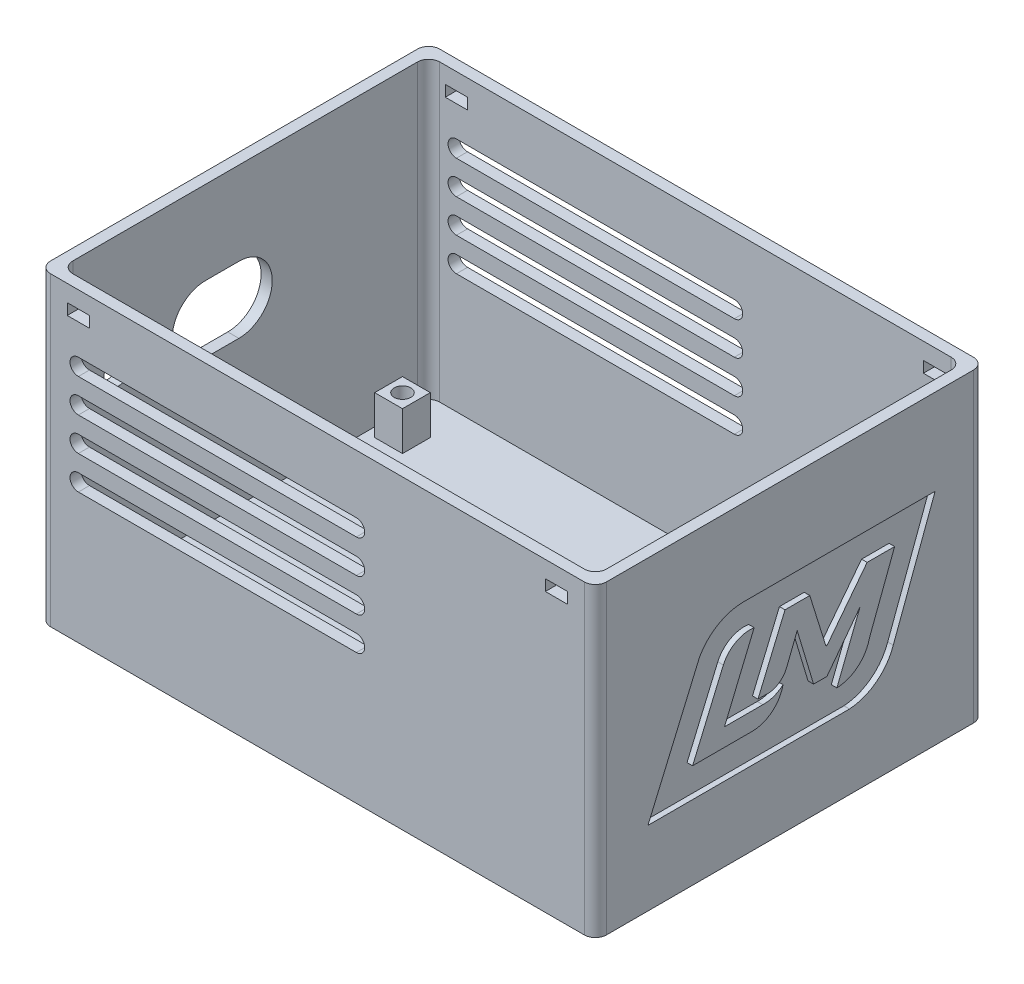
SolidWorks part; units mm, degrees
ref_plane "Front Plane" through (0, 0, 0) normal (0, 0, 1) x (1, 0, 0)
ref_plane "Top Plane" through (0, 0, 0) normal (0, 1, 0) x (1, 0, 0)
ref_plane "Right Plane" through (0, 0, 0) normal (1, 0, 0) x (0, 0, -1)
sketch "Sketch1" plane through (0, 0, 0) normal (0, 1, 0) x (1, 0, 0)
  line L1 (-50, 35) -> (50, 35)
  line L2 (-50, 35) -> (-50, -35)
  line L3 (-50, -35) -> (50, -35)
  line L4 (50, 35) -> (50, -35)
  line L5 (-50, 35) -> (50, -35) construction
  line L6 (-50, -35) -> (50, 35) construction
  point P0 (0, 0)
  dimension "D1" = 100
  dimension "D2" = 70
extrude "Boss-Extrude1" add sketch "Sketch1" along normal blind 2
sketch "Sketch3" plane through (0, 0, 0) normal (0, -1, 0) x (1, 0, 0)
  line L4 (50, -35) -> (50, 35)
  line L5 (50, 35) -> (-50, 35)
  line L6 (-50, 35) -> (-50, -35)
  line L7 (-50, -35) -> (50, -35)
  line L8 (50, -35) -> (50, 35)
  line L9 (50, 35) -> (-50, 35)
  line L10 (-50, 35) -> (-50, -35)
  line L11 (-50, -35) -> (50, -35)
  line L12 (50, -35) -> (50, 35)
  line L13 (-50, -35) -> (50, -35)
  line L14 (-50, 35) -> (-50, -35)
  line L15 (50, 35) -> (-50, 35)
  line L16 (50, -35) -> (50, 35)
  line L17 (-50, -35) -> (50, -35)
  line L18 (-50, 35) -> (-50, -35)
  line L19 (50, 35) -> (-50, 35)
  line L24 (48, -33) -> (48, 33)
  line L25 (-48, -33) -> (48, -33)
  line L26 (-48, 33) -> (-48, -33)
  line L27 (48, 33) -> (-48, 33)
  line L28 (48, -33) -> (48, 33)
  line L29 (-48, -33) -> (48, -33)
  line L30 (-48, 33) -> (-48, -33)
  line L31 (48, 33) -> (-48, 33)
  line M13 (50, -35) -> (50, 35)
  line M14 (50, 35) -> (-50, 35)
  line M15 (-50, 35) -> (-50, -35)
  line M16 (-50, -35) -> (50, -35)
  dimension "D1" = 0
  dimension "D2" = 0
  dimension "D3" = 2
extrude "Boss-Extrude2" add sketch "Sketch3" against normal blind 55 contours L31 L28 L29 L30 M16 M13 M14 M15
fillet "Fillet1" radius 2 8 edges at (48, 28.5, 33) (-48, 28.5, 33) (-50, 27.5, 35) (50, 27.5, 35) (48, 28.5, -33) (50, 27.5, -35) (-50, 27.5, -35) (-48, 28.5, -33)
sketch "Sketch4" plane through (0, 2, 0) normal (0, 1, 0) x (1, 0, 0)
  line L0 (25, 0) -> (-43.83, 0) construction
  line L1 (-43.83, 24.13) -> (25, 24.13) construction
  line L2 (-43.83, 24.13) -> (-43.83, -24.13) construction
  line L3 (-43.83, -24.13) -> (25, -24.13) construction
  line L4 (25, 24.13) -> (25, -24.13) construction
  line L5 (48, -31) -> (48, 31) construction
  line L7 (31, 24.13) -> (48, 24.13) construction
  line L8 (31, 24.13) -> (31, -1.87) construction
  line L9 (31, -1.87) -> (48, -1.87) construction
  line L10 (48, 24.13) -> (48, -1.87) construction
  line L11 (-48, 31) -> (-48, -31) construction
  dimension "D1" = 68.83
  dimension "D2" = 48.26
  dimension "D3" = 23
  dimension "D4" = 17
  dimension "D5" = 6
  dimension "D6" = 26
  dimension "D7" = 24.13
  dimension "D8" = 4.17
sketch "Sketch5" plane through (0, 2, 0) normal (0, 1, 0) x (1, 0, 0)
  line L1 (-41.33, 26.63) -> (-46.33, 26.63)
  line L2 (-41.33, 26.63) -> (-41.33, 21.63)
  line L3 (-41.33, 21.63) -> (-46.33, 21.63)
  line L4 (-46.33, 26.63) -> (-46.33, 21.63)
  line L5 (-41.33, 26.63) -> (-46.33, 21.63) construction
  line L6 (-41.33, 21.63) -> (-46.33, 26.63) construction
  line L7 (-9.415, 24.13) -> (-9.415, -24.13) construction
  line L8 (-43.83, 24.13) -> (25, 24.13) construction
  line L9 (-43.83, -24.13) -> (25, -24.13) construction
  line L10 (25, 0) -> (-43.83, 0) construction
  line L11 (22.5, 21.63) -> (27.5, 21.63)
  line L12 (27.5, 26.63) -> (27.5, 21.63)
  line L13 (22.5, 26.63) -> (27.5, 26.63)
  line L14 (22.5, 26.63) -> (22.5, 21.63)
  line L15 (22.5, -26.63) -> (22.5, -21.63)
  line L16 (22.5, -26.63) -> (27.5, -26.63)
  line L17 (27.5, -26.63) -> (27.5, -21.63)
  line L18 (22.5, -21.63) -> (27.5, -21.63)
  line L19 (-41.33, -21.63) -> (-46.33, -21.63)
  line L20 (-46.33, -26.63) -> (-46.33, -21.63)
  line L21 (-41.33, -26.63) -> (-46.33, -26.63)
  line L22 (-41.33, -26.63) -> (-41.33, -21.63)
  point P0 (-43.83, 24.13)
  dimension "D1" = 5
  dimension "D2" = 5
extrude "Boss-Extrude3" add sketch "Sketch5" along normal blind 7
sketch "Sketch6" plane through (0, 9, 0) normal (0, 1, 0) x (1, 0, 0)
  line L0 (-9.415, 24.13) -> (-9.415, -24.13) construction
  line L1 (-43.83, 24.13) -> (25, 24.13) construction
  line L2 (-43.83, -24.13) -> (25, -24.13) construction
  line L3 (-43.83, 0) -> (25, 0) construction
  circle A0 centre (-43.83, 24.13) radius 1.5
  circle A1 centre (25, 24.13) radius 1.5
  circle A2 centre (25, -24.13) radius 1.5
  circle A3 centre (-43.83, -24.13) radius 1.5
  dimension "D1" = 3
extrude "Cut-Extrude1" cut sketch "Sketch6" against normal blind 5
sketch "Sketch7" plane through (-50, 0, 0) normal (-1, 0, 0) x (0, 0, 1)
  line L1 (-24.13, 2) -> (24.13, 2) construction
  line L2 (-24.13, 2) -> (1.87, 2) construction
  line L3 (1.13, 34) -> (7.13, 34) construction
  line L4 (1.13, 40) -> (7.13, 40)
  line L5 (1.13, 28) -> (7.13, 28)
  arc A1 (1.13, 40) -> (1.13, 28) centre (1.13, 34) ccw
  arc A2 (7.13, 28) -> (7.13, 40) centre (7.13, 34) ccw
  point P0 (13.13, 34)
  point P1 (-4.87, 34)
  point P2 (-24.13, 2)
  point P3 (4.13, 34)
  point P6 (24.13, 2)
  dimension "D1" = 32
  dimension "D2" = 20
  dimension "D4" = 18
  dimension "D5" = 24.13
  dimension "D3" = 24.13
  dimension "D7" = 12
extrude "Cut-Extrude2" cut sketch "Sketch7" against normal up to surface (2 mm away) up to face at (-48, 28.5, 0)
sketch "Sketch8" plane through (0, 2, 0) normal (0, 1, 0) x (1, 0, 0)
  line L0 (48, 24.13) -> (31, 24.13)
  line L1 (31, 24.13) -> (31, -1.87)
  line L2 (31, -1.87) -> (48, -1.87)
  line L3 (48, -1.87) -> (48, -3.87)
  line L4 (48, 31) -> (48, -31) construction
  line L5 (48, 26.13) -> (29, 26.13)
  line L6 (29, 26.13) -> (29, -3.87)
  line L7 (29, -3.87) -> (48, -3.87)
  line L9 (48, 26.13) -> (48, 24.13)
  line L10 (48, -1.87) -> (48, -3.87)
  point P15 (0, 0)
  line M9 (48, -31) -> (48, 31)
  dimension "D1" = 2
extrude "Boss-Extrude4" add sketch "Sketch8" along normal blind 25 contours L6 L7 L2 L1 L0 L5 M9
fillet "Fillet2" radius 1 8 edges at (31, 14.5, 1.87) (29, 14.5, 3.87) (48, 14.5, 3.87) (48, 14.5, 1.87) (48, 14.5, -26.13) (48, 14.5, -24.13) (29, 14.5, -26.13) (31, 14.5, -24.13)
sketch "Sketch12" plane through (0, 0, 35) normal (0, 0, 1) x (1, 0, 0)
  line L0 (-43, 25) -> (7, 25) construction
  line L1 (-43, 26.5) -> (7, 26.5)
  line L2 (-43, 23.5) -> (7, 23.5)
  line L3 (-48, 0) -> (48, 0) construction
  line L4 (-43, 29.5) -> (7, 29.5)
  line L5 (-50, 0) -> (-50, 55) construction
  line L6 (-43, 32.5) -> (7, 32.5)
  line L7 (-43, 31) -> (7, 31) construction
  line L8 (-43, 35.5) -> (7, 35.5)
  line L9 (-43, 38.5) -> (7, 38.5)
  line L10 (-43, 37) -> (7, 37) construction
  line L11 (-43, 41.5) -> (7, 41.5)
  line L12 (-43, 44.5) -> (7, 44.5)
  line L13 (-43, 43) -> (7, 43) construction
  arc A0 (-43, 26.5) -> (-43, 23.5) centre (-43, 25) ccw
  arc A1 (7, 23.5) -> (7, 26.5) centre (7, 25) ccw
  arc A2 (-43, 32.5) -> (-43, 29.5) centre (-43, 31) ccw
  arc A3 (7, 29.5) -> (7, 32.5) centre (7, 31) ccw
  arc A4 (-43, 38.5) -> (-43, 35.5) centre (-43, 37) ccw
  arc A5 (7, 35.5) -> (7, 38.5) centre (7, 37) ccw
  arc A6 (-43, 44.5) -> (-43, 41.5) centre (-43, 43) ccw
  arc A7 (7, 41.5) -> (7, 44.5) centre (7, 43) ccw
  point P2 (-18, 25)
  point P15 (-18, 31)
  point P22 (-18, 37)
  point P29 (-18, 43)
  dimension "D4" = 7
  dimension "D1" = 25
  dimension "D2" = 50
  dimension "D3" = 3
  dimension "D5" = 4
extrude "Cut-Extrude3" cut sketch "Sketch12" against normal through all contours L11 A7 L12 A6 | L8 A5 L9 A4 | L4 A3 L6 A2 | L2 A1 L1 A0
sketch "Sketch13" plane through (-50, 0, 0) normal (-1, 0, 0) x (0, 0, 1)
  text T0 "<b>LOG</b>" font "Century Gothic" height 5
  point P1 (18.1408, 21.9684)
  point P2 (0, 0)
  point P3 (18.9654, 23.8925)
  point P4 (16.6978, 22.312)
  point P5 (0, 0)
  point P6 (0, 0)
  point P7 (-25.2184, 28.9087)
  point P8 (15.5296, 25.8852)
  point P9 (0, 0)
  point P10 (15.5296, 24.0299)
  point P11 (15.5296, 22.2433)
  point P12 (15.7358, 20.7316)
  point P13 (0, 0)
  point P14 (0, 0)
  point P15 (15.3235, 20.9377)
extrude "Cut-Extrude4" cut sketch "Sketch13" against normal blind 1
sketch "Sketch15" plane through (-49, 0, 0) normal (-1, 0, 0) x (0, 0, 1)
  line L0 (29.7395, 23.5018) -> (15.9004, 23.4377) construction
  line L1 (15.9004, 20.9377) -> (15.9004, 25.9377) construction
  point P5 (18.6757, 24.2463)
sketch "Sketch16" plane through (-50, 0, 0) normal (-1, 0, 0) x (0, 0, 1)
  line L0 (29.7395, 23.5018) -> (15.9004, 23.4377) construction
  line L1 (15.82, 26.9698) -> (29.82, 26.9698)
  line L2 (14.82, 25.9698) -> (14.82, 20.9698)
  line L3 (15.82, 19.9698) -> (29.82, 19.9698)
  line L4 (30.82, 25.9698) -> (30.82, 20.9698)
  line L5 (14.82, 26.9698) -> (30.82, 19.9698) construction
  line L6 (14.82, 19.9698) -> (30.82, 26.9698) construction
  line L7 (13.82, 25.9698) -> (13.82, 20.9698)
  line L8 (15.82, 18.9698) -> (29.82, 18.9698)
  line L9 (31.82, 25.9698) -> (31.82, 20.9698)
  line L10 (15.82, 27.9698) -> (29.82, 27.9698)
  arc A0 (29.82, 19.9698) -> (30.82, 20.9698) centre (29.82, 20.9698) ccw
  arc A1 (29.82, 26.9698) -> (30.82, 25.9698) centre (29.82, 25.9698) cw
  arc A2 (15.82, 26.9698) -> (14.82, 25.9698) centre (15.82, 25.9698) ccw
  arc A3 (14.82, 20.9698) -> (15.82, 19.9698) centre (15.82, 20.9698) ccw
  arc A4 (13.82, 20.9698) -> (15.82, 18.9698) centre (15.82, 20.9698) ccw
  arc A5 (29.82, 18.9698) -> (31.82, 20.9698) centre (29.82, 20.9698) ccw
  arc A6 (29.82, 27.9698) -> (31.82, 25.9698) centre (29.82, 25.9698) cw
  arc A7 (15.82, 27.9698) -> (13.82, 25.9698) centre (15.82, 25.9698) ccw
  point P0 (22.8019, 23.4573)
  point P1 (22.82, 23.4698)
  dimension "D3" = 1
  dimension "D4" = 1
  dimension "D1" = 7
  dimension "D2" = 16
  dimension "D5" = 1
extrude "Cut-Extrude5" cut sketch "Sketch16" against normal blind 1
sketch "Sketch17" plane through (-50, 0, 0) normal (-1, 0, 0) x (0, 0, 1)
  line L0 (29.7395, 23.5018) -> (15.9004, 23.4377) construction
  circle A0 centre (22.82, 34) radius 2.6
  arc A1 (7.13, 28) -> (7.13, 40) centre (7.13, 34) ccw construction
  point P4 (22.82, 23.4698)
  point P8 (0, 0)
  point P9 (13.13, 34)
  dimension "D1" = 5.2
extrude "Cut-Extrude6" cut sketch "Sketch17" against normal up to surface (2 mm away) up to face at (-48, 34, 4.13)
sketch "Sketch19" plane through (50, 0, 0) normal (1, 0, 0) x (0, 0, -1)
  line L0 (71.1667, 226.8303) -> (455.8333, 226.8303) construction
  line L1 (224, 504) -> (1120, 504) construction
  line L2 (82, 257) -> (530, 257) construction
  line L3 (-6.4381, 34.594) -> (-11.787, 21.8116)
  line L4 (-11.787, 21.8116) -> (-4.9042, 21.8116)
  line L5 (-6.8559, 18.6116) -> (-17.5155, 18.6116)
  line L6 (-17.5155, 18.6116) -> (-11.9833, 31.5425)
  line L7 (-0.8925, 34.594) -> (-5.7477, 23.1095)
  line L8 (-5.7477, 23.1095) -> (-4.5185, 23.1095)
  line L9 (1.3022, 30.2627) -> (-0.5959, 25.4724)
  line L10 (1.3022, 30.2627) -> (4.2486, 20.4472)
  line L11 (4.2486, 20.4472) -> (6.6528, 20.4472)
  line L12 (6.6528, 20.4472) -> (12.6145, 28.3085)
  line L13 (12.6145, 28.3085) -> (8.4379, 17.7676)
  line L14 (14.2872, 22.5976) -> (18.8287, 34.594)
  line L15 (18.8287, 34.594) -> (13.879, 34.594)
  line L16 (13.879, 34.594) -> (6.6528, 25.2426)
  line L17 (6.6528, 25.2426) -> (6.4793, 25.2426)
  line L18 (6.4793, 25.2426) -> (3.5604, 34.594)
  line L19 (3.5604, 34.594) -> (-0.8925, 34.594)
  line L20 (26.1103, 39.5611) -> (-8.4395, 39.5611)
  line L21 (-16.2529, 34.9444) -> (-25.5494, 13.3426)
  line L22 (-25.5494, 13.3426) -> (10.7063, 13.3426)
  line L23 (26.1103, 39.5611) -> (18.5852, 19.3547)
  arc A0 (-4.9042, 21.8116) -> (-1.2465, 23.1095) centre (-4.6755, 26.97) ccw
  arc A1 (-1.2465, 23.1095) -> (-6.8559, 18.6116) centre (-6.821, 24.3148) cw
  arc A2 (-6.4381, 34.594) -> (-11.9833, 31.5425) centre (-7.1826, 29.3826) ccw
  arc A3 (-4.5185, 23.1095) -> (-0.5959, 25.4724) centre (-4.0785, 26.8164) ccw
  arc A4 (8.4379, 17.7676) -> (14.2872, 22.5976) centre (8.2574, 23.943) ccw
  arc A5 (-8.4395, 39.5611) -> (-16.2529, 34.9444) centre (-8.3276, 30.4515) ccw
  arc A6 (10.7063, 13.3426) -> (18.5852, 19.3547) centre (10.1245, 22.2738) ccw
extrude "Cut-Extrude7" cut sketch "Sketch19" against normal blind 1
sketch "Sketch20" plane through (0, 0, 35) normal (0, 0, 1) x (1, 0, 0)
  line L0 (0, 55) -> (0, 0) construction
  line L1 (-45, 52) -> (-41, 52)
  line L2 (-45, 52) -> (-45, 50)
  line L3 (-45, 50) -> (-41, 50)
  line L4 (-41, 52) -> (-41, 50)
  line L5 (48, 55) -> (-48, 55) construction
  line L6 (-50, 0) -> (-50, 55) construction
  line L7 (45, 50) -> (41, 50)
  line L8 (41, 52) -> (41, 50)
  line L9 (45, 52) -> (41, 52)
  line L10 (45, 52) -> (45, 50)
  dimension "D1" = 4
  dimension "D2" = 2
  dimension "D3" = 3
  dimension "D4" = 5
extrude "Cut-Extrude8" cut sketch "Sketch20" against normal through all
